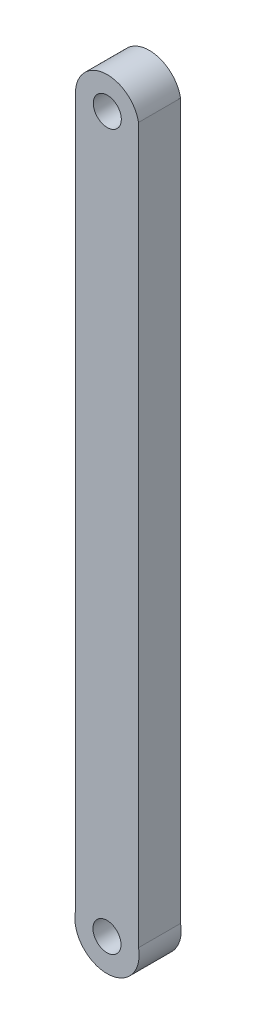
SolidWorks part; units mm, degrees
ref_plane "前视基准面" through (0, 0, 0) normal (0, 0, 1) x (1, 0, 0)
ref_plane "上视基准面" through (0, 0, 0) normal (0, 1, 0) x (1, 0, 0)
ref_plane "右视基准面" through (0, 0, 0) normal (1, 0, 0) x (0, 0, -1)
sketch "草图1" plane through (0, 0, 0) normal (0, 0, 1) x (1, 0, 0)
  line L0 (-2.4, 50.5639) -> (-2.4, 0.0197)
  line L1 (2.1, 0) -> (2.1, 50.996)
  arc A0 (2.1, 50.996) -> (-2.4, 50.5639) centre (-0.1293, 50.5639) ccw
  arc A1 (-2.4, 0.0197) -> (2.1, 0) centre (-0.152, -0.4361) ccw
  circle A2 centre (-0.152, -0.4361) radius 1
  circle A5 centre (-0.1293, 50.5639) radius 1
  point P5 (0, 0)
  point P7 (0, 0)
  dimension "D2" = 2
  dimension "D3" = 2
  dimension "D1" = 51
  dimension "D4" = 4.5
extrude "凸台-拉伸1" add sketch "草图1" along normal blind 3
